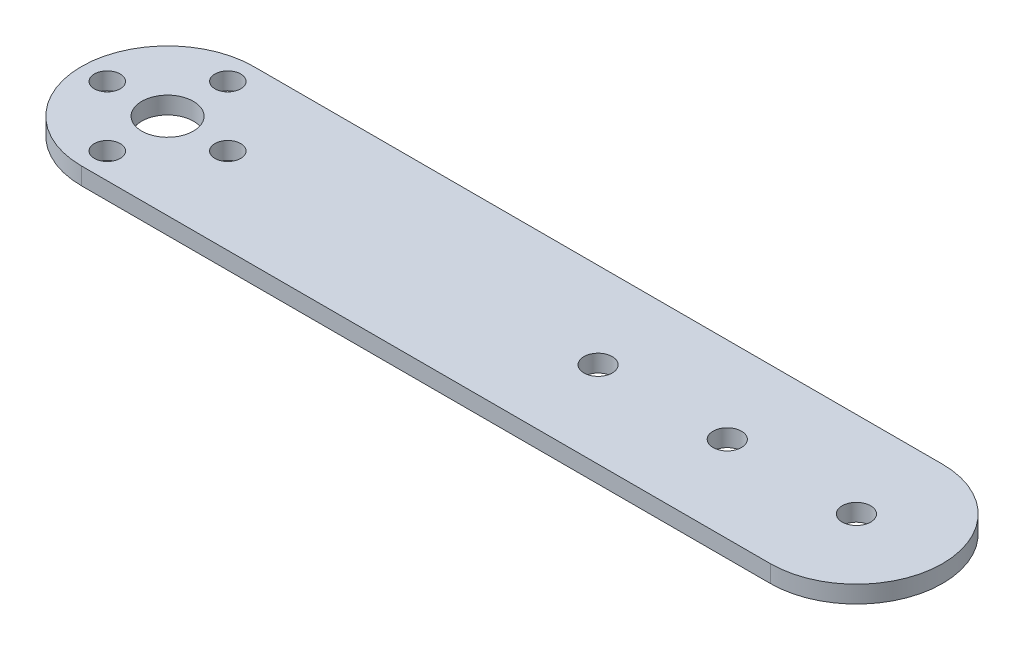
SolidWorks part; units mm, degrees
material "1060 Сплав"
ref_plane "Спереди" through (0, 0, 0) normal (0, 0, 1) x (1, 0, 0)
ref_plane "Сверху" through (0, 0, 0) normal (0, 1, 0) x (1, 0, 0)
ref_plane "Справа" through (0, 0, 0) normal (1, 0, 0) x (0, 0, -1)
sketch "Эскиз1" plane through (0, 0, 0) normal (0, 1, 0) x (1, 0, 0)
  line L0 (0, 10) -> (80, 10)
  line L1 (0, -10) -> (80, -10)
  arc A0 (0, 10) -> (0, -10) centre (0, 0) ccw
  circle A1 centre (0, 0) radius 7 construction
  circle A2 centre (0, 7) radius 1.5
  circle A3 centre (7, 0) radius 1.5
  circle A4 centre (0, -7) radius 1.5
  circle A5 centre (-7, 0) radius 1.5
  arc A6 (80, 10) -> (80, -10) centre (80, 0) cw
  circle A7 centre (80, 0) radius 1.65
  circle A8 centre (50, 0) radius 1.65
  circle A9 centre (65, 0) radius 1.65
  circle A13 centre (0, 0) radius 3
  point P18 (65, 0)
  point P24 (80, 0)
  point P31 (80, 0)
  dimension "D1" = 14
  dimension "D2" = 3
  dimension "D3" = 20
  dimension "D4" = 80
  dimension "D5" = 30
  dimension "D7" = 6
  dimension "D6" = 3.3
  dimension "D9" = 65
extrude "Бобышка-Вытянуть1" add sketch "Эскиз1" along normal blind 2
